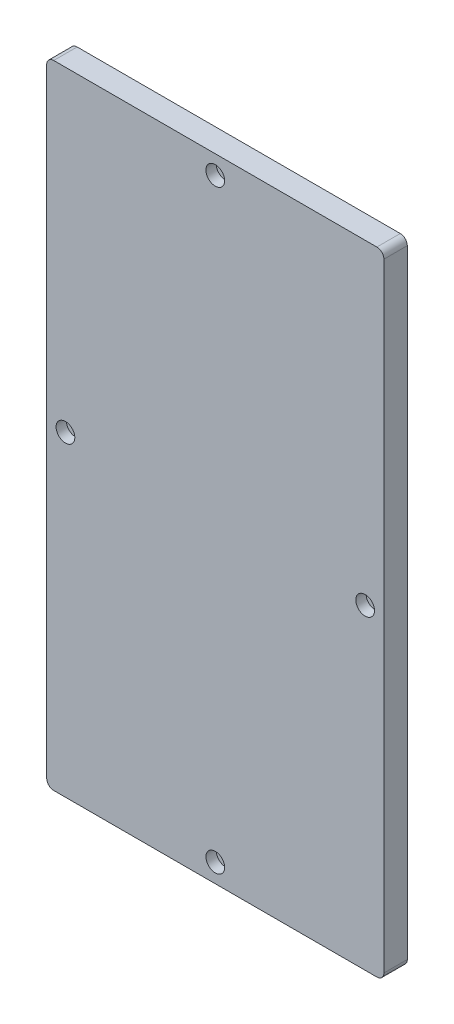
SolidWorks part; units mm, degrees
material "ABS"
ref_plane "Front Plane" through (0, 0, 0) normal (0, 0, 1) x (1, 0, 0)
ref_plane "Top Plane" through (0, 0, 0) normal (0, 1, 0) x (1, 0, 0)
ref_plane "Right Plane" through (0, 0, 0) normal (1, 0, 0) x (0, 0, -1)
sketch "Sketch1" plane through (0, 0, 0) normal (0, 0, 1) x (1, 0, 0)
  line L1 (72, -135) -> (-72, -135)
  line L2 (72, -135) -> (72, 135)
  line L3 (72, 135) -> (-72, 135)
  line L4 (-72, -135) -> (-72, 135)
  line L5 (72, -135) -> (-72, 135) construction
  line L6 (72, 135) -> (-72, -135) construction
  point P0 (0, 0)
  dimension "D1" = 144
  dimension "D2" = 270
extrude "Boss-Extrude1" add sketch "Sketch1" along normal blind 10
hole_wizard "CBORE for M4 Hex Socket Head Cap Screw1" positions "Sketch2" profile "Sketch3" counterbore size "M4" standard "DIN" end condition up to next
sketch "Sketch2" plane through (0, 0, 10) normal (0, 0, 1) x (1, 0, 0)
  line L20 (-64, 127) -> (-64, -127)
  line L21 (-64, -127) -> (64, -127)
  line L22 (64, -127) -> (64, 127)
  line L23 (64, 127) -> (-64, 127)
  line L24 (-64, 127) -> (-64, -127) construction
  line L25 (-64, -127) -> (64, -127) construction
  line L26 (64, -127) -> (64, 127) construction
  line L27 (64, 127) -> (-64, 127) construction
  point P0 (0, 127)
  point P7 (-64, 0)
  point P16 (0, -127)
  point P54 (64, 0)
  dimension "D4" = 8
sketch "Sketch3" plane through (0, 127, 10) normal (1, 0, 0) x (0, -1, 0)
  line L0 (0, 0) -> (0, 10)
  line L1 (2.25, 9.975) -> (2.275, 10)
  line L2 (2.25, 9.975) -> (2.25, 4.4)
  line L3 (2.25, 4.4) -> (4, 4.4)
  line L4 (4, 4.4) -> (4, 0)
  line L5 (4, 0) -> (0, 0)
  line L11 (0, -6.35) -> (0, 107.95) construction
  line L12 (2.275, 10) -> (0, 10)
  line L13 (-2.25, 9.975) -> (-2.275, 10) construction
  dimension "Thru Hole Dia." = 4.5
  dimension "Thru Hole Depth" = 10
  dimension "C'Bore Dia." = 8
  dimension "C'Bore Depth" = 4.4
  dimension "Far C'Sink Dia." = 4.55
  dimension "Far C'Sink Angle" = 90
sketch "Sketch4" plane through (0, 0, 10) normal (0, 0, 1) x (1, 0, 0)
  line L14 (-67, -130) -> (67, -130)
  line L15 (67, -130) -> (67, 130)
  line L16 (67, 130) -> (-67, 130)
  line L17 (-67, 130) -> (-67, -130)
  line L18 (-67, -130) -> (67, -130)
  line L19 (67, -130) -> (67, 130)
  line L20 (67, 130) -> (-67, 130)
  line L21 (-67, 130) -> (-67, -130)
  arc A0 (-6.3246, 130) -> (6.3246, 130) centre (0, 127) ccw
  arc A2 (-67, -6.3246) -> (-67, 6.3246) centre (-64, 0) ccw
  arc A4 (-6.3246, -130) -> (6.3246, -130) centre (0, -127) cw
  arc A6 (67, -6.3246) -> (67, 6.3246) centre (64, 0) cw
  circle A7 centre (0, 127) radius 4 construction
  point P25 (-7.4162, 130)
  dimension "D2" = 3
  dimension "D1" = 5
extrude "Cut-Extrude1" cut sketch "Sketch4" against normal up to next from offset 5 contours L18 A4 L19 L20 A0 L21 A2 offset against normal yes
fillet "Fillet1" radius 3 4 edges at (-72, 135, 5) (-72, -135, 5) (72, -135, 5) (72, 135, 5)
